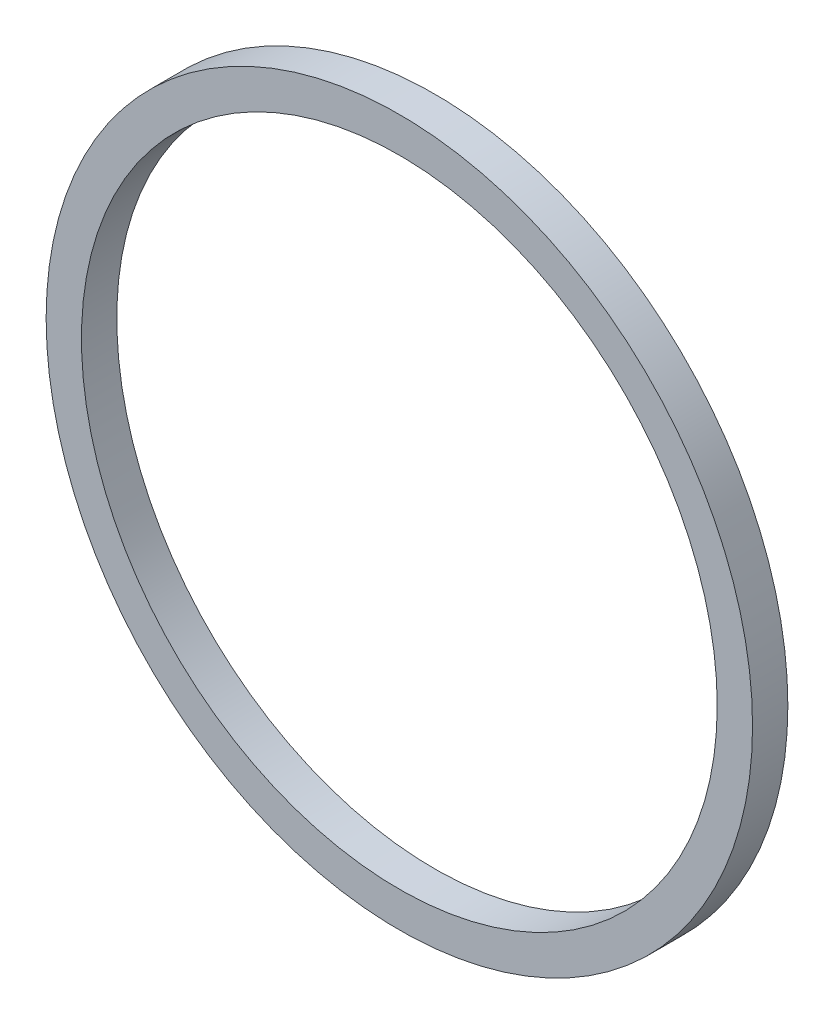
SolidWorks part; units mm, degrees
material "AISI 304"
ref_plane "前视基准面" through (0, 0, 0) normal (0, 0, 1) x (1, 0, 0)
ref_plane "上视基准面" through (0, 0, 0) normal (0, 1, 0) x (1, 0, 0)
ref_plane "右视基准面" through (0, 0, 0) normal (1, 0, 0) x (0, 0, -1)
other "Configuration Table"
sketch "草图1" plane through (0, 0, 0) normal (0, 0, 1) x (1, 0, 0)
  circle A0 centre (0, 0) radius 57.15
  circle A1 centre (0, 0) radius 63.5
  dimension "D1" = 114.3
  dimension "D2" = 127
extrude "凸台-拉伸1" add sketch "草图1" along normal blind 6.35
